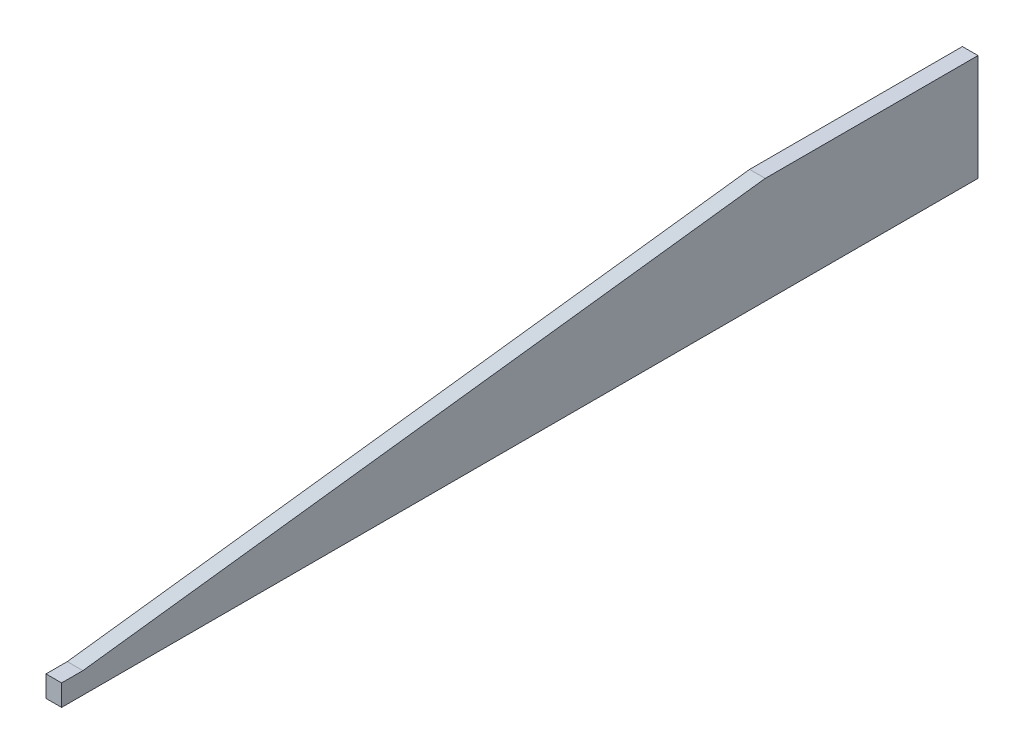
SolidWorks part; units mm, degrees
ref_plane "Plan de face" through (0, 0, 0) normal (0, 0, 1) x (1, 0, 0)
ref_plane "Plan de dessus" through (0, 0, 0) normal (0, 1, 0) x (1, 0, 0)
ref_plane "Plan de droite" through (0, 0, 0) normal (1, 0, 0) x (0, 0, -1)
sketch "Esquisse1" plane through (0, 0, 0) normal (0, 0, 1) x (1, 0, 0)
  line L1 (-11, 75) -> (11, 75)
  line L2 (-11, 75) -> (-11, -75)
  line L3 (-11, -75) -> (11, -75)
  line L4 (11, 75) -> (11, -75)
  line L5 (-11, 75) -> (11, -75) construction
  line L6 (-11, -75) -> (11, 75) construction
  point P4 (0, 0)
  dimension "D1" = 22
  dimension "D2" = 150
extrude "Boss.-Extru.1" add sketch "Esquisse1" along normal blind 1292
sketch "Esquisse2" plane through (11, 0, 0) normal (1, 0, 0) x (0, 0, -1)
  line L0 (-300, 75) -> (-1262, -45)
  line L1 (-1292, 75) -> (0, 75) construction
  line L2 (-1262, -45) -> (-1292, -45)
  line L3 (-1292, -75) -> (-1292, 75) construction
  line L4 (-1292, -45) -> (-1292, 75)
  line L5 (-1292, 75) -> (-300, 75)
  line L6 (0, -75) -> (0, 75) construction
  line L7 (-1292, -75) -> (0, -75) construction
  dimension "D1" = 300
  dimension "D2" = 30
  dimension "D3" = 30
extrude "Enlèv. mat.-Extru.1" cut sketch "Esquisse2" against normal through all
